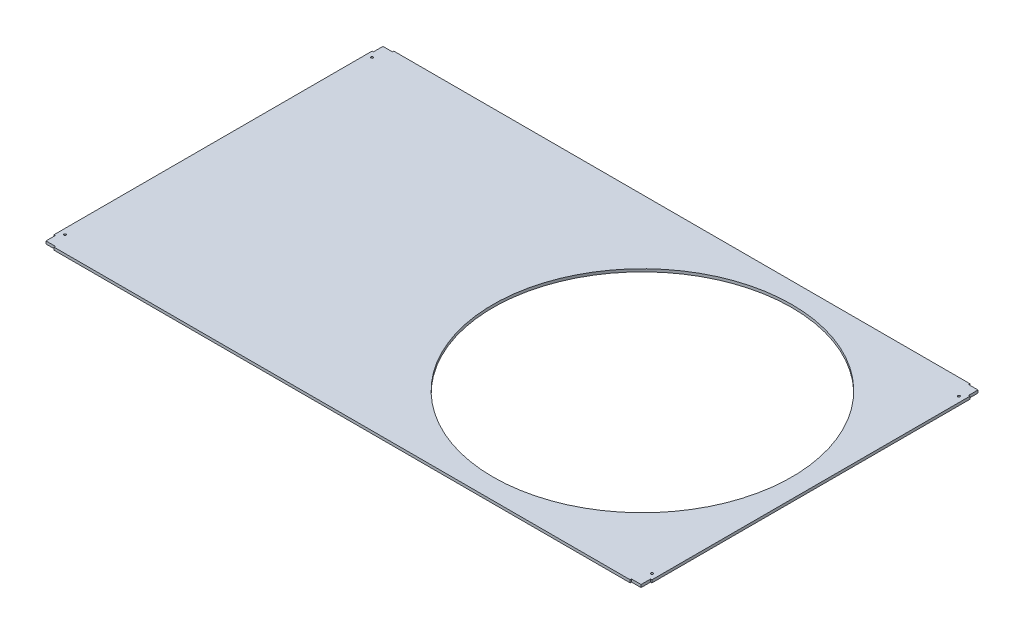
SolidWorks part; units mm, degrees
ref_plane "前视基准面" through (0, 0, 0) normal (0, 0, 1) x (1, 0, 0)
ref_plane "上视基准面" through (0, 0, 0) normal (0, 1, 0) x (1, 0, 0)
ref_plane "右视基准面" through (0, 0, 0) normal (1, 0, 0) x (0, 0, -1)
sketch "草图1" plane through (0, 0, 0) normal (0, 1, 0) x (1, 0, 0)
  line L1 (-1100, 625) -> (1100, 625)
  line L2 (-1100, 625) -> (-1100, -625)
  line L3 (-1100, -625) -> (1100, -625)
  line L4 (1100, 625) -> (1100, -625)
  circle A0 centre (480, 0) radius 550
  dimension "D5" = 625
  dimension "D7" = 1100
  dimension "D1" = 2200
  dimension "D2" = 1250
  dimension "D3" = 625
  dimension "D4" = 1100
  dimension "D6" = 620
extrude "凸台-拉伸1" add sketch "草图1" along normal blind 10
sketch "草图2" plane through (0, 10, 0) normal (0, 1, 0) x (1, 0, 0)
  line L0 (1100, 625) -> (-1100, 625) construction
  line L1 (-1100, 625) -> (-1100, -625) construction
  line L2 (-1100, -625) -> (1100, -625) construction
  line L3 (1100, -625) -> (1100, 625) construction
  circle A0 centre (-1080, 565) radius 4.05
  circle A1 centre (-1080, -565) radius 4.05
  circle A2 centre (1080, -565) radius 4.05
  circle A3 centre (1080, 565) radius 4.05
  point P8 (-1066.8001, 543.477)
  point P9 (-1046.651, -581.1105)
  point P14 (1068.6323, -590)
  point P19 (1075, 590)
  point P20 (0, 0)
  dimension "D1" = 60
  dimension "D2" = 20
  dimension "D3" = 60
  dimension "D4" = 20
  dimension "D5" = 20
  dimension "D6" = 60
  dimension "D7" = 60
  dimension "D8" = 20
extrude "切除-拉伸1" cut sketch "草图2" against normal blind 10
sketch "草图3" plane through (0, 10, 0) normal (0, 1, 0) x (1, 0, 0)
  line L0 (-1100, 625) -> (-1060, 625)
  line L1 (1100, 625) -> (-1100, 625) construction
  line L2 (-1060, 625) -> (-1060, 620)
  line L3 (-1060, 620) -> (-1095, 620)
  line L4 (-1095, 620) -> (-1095, 585)
  line L5 (-1095, 585) -> (-1100, 585)
  line L6 (-1100, 625) -> (-1100, -625) construction
  line L7 (-1100, 585) -> (-1100, 625)
  line L8 (-55, 0) -> (55, 0) construction
  line L9 (-1100, -585) -> (-1100, -625)
  line L10 (-1095, -585) -> (-1100, -585)
  line L11 (-1095, -620) -> (-1095, -585)
  line L12 (-1060, -620) -> (-1095, -620)
  line L13 (-1060, -625) -> (-1060, -620)
  line L14 (-1100, -625) -> (-1060, -625)
  line L15 (0, -55) -> (0, 55) construction
  line L16 (1100, -625) -> (1060, -625)
  line L17 (1060, -625) -> (1060, -620)
  line L18 (1060, -620) -> (1095, -620)
  line L19 (1095, -620) -> (1095, -585)
  line L20 (1095, -585) -> (1100, -585)
  line L21 (1100, -585) -> (1100, -625)
  line L22 (1100, 585) -> (1100, 625)
  line L23 (1095, 585) -> (1100, 585)
  line L24 (1095, 620) -> (1095, 585)
  line L25 (1060, 620) -> (1095, 620)
  line L26 (1060, 625) -> (1060, 620)
  line L27 (1100, 625) -> (1060, 625)
extrude "切除-拉伸2" cut sketch "草图3" against normal blind 10
